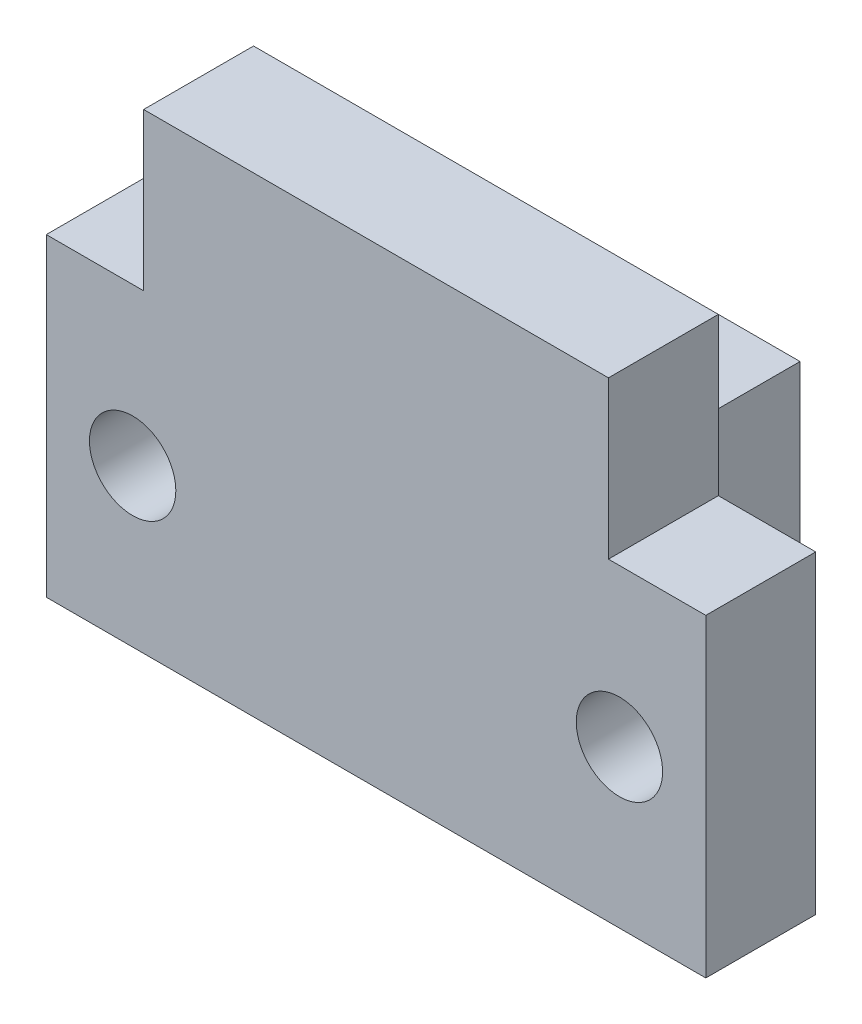
SolidWorks part; units mm, degrees
other "Encoder Spring mount spacer"
other "Encoder Spring mount"
ref_plane "Front Plane" through (0, 0, 0) normal (0, 0, 1) x (1, 0, 0)
ref_plane "Top Plane" through (0, 0, 0) normal (0, 1, 0) x (1, 0, 0)
ref_plane "Right Plane" through (0, 0, 0) normal (1, 0, 0) x (0, 0, -1)
sketch "Sketch1" plane through (0, 0, 0) normal (0, 1, 0) x (1, 0, 0)
  line L0 (10, 13.5) -> (4, 13.5)
  line L2 (21, -3.5) -> (-21, -3.5)
  line L4 (21, -3.5) -> (21, 3.5)
  line L10 (21, 3.5) -> (-21, 3.5)
  line L11 (-21, -3.5) -> (-21, 3.5)
  line L12 (0, 3.5) -> (0, -3.5) construction
  line L13 (21, 0) -> (-21, 0) construction
  line L14 (-10, 3.5) -> (-4, 3.5)
  line L15 (-10, 3.5) -> (-10, 13.5)
  line L16 (-10, 13.5) -> (-4, 13.5)
  line L17 (-4, 3.5) -> (-4, 13.5)
  line L18 (4, 3.5) -> (4, 13.5)
  line L19 (10, 3.5) -> (4, 3.5)
  line L20 (10, 3.5) -> (10, 13.5)
  point P0 (0, 0)
  dimension "D1" = 7
  dimension "D3" = 6
  dimension "D2" = 42
  dimension "D4" = 4
  dimension "D5" = 10
extrude "Boss-Extrude1" add sketch "Sketch1" along normal blind 20 contours L11 L2 L4 L10 | L10 L17 L16 L15 | L20 L0 L18 L19
sketch "Sketch6" plane through (0, 0, -3.5) normal (0, 0, -1) x (-1, 0, 0)
  line L0 (-10, 10) -> (-21, 10) construction
  line L1 (-10, 20) -> (-10, 0) construction
  line L2 (-21, 20) -> (-21, 0) construction
  line L3 (0, 0) -> (0, 20) construction
  line L4 (-4, 20) -> (4, 20) construction
  line L5 (10, 10) -> (21, 10) construction
  circle A0 centre (-15.5, 10) radius 2.75
  circle A1 centre (15.5, 10) radius 2.75
  dimension "D1" = 5.5
extrude "Cut-Extrude4" cut sketch "Sketch6" against normal through all
sketch "Sketch7" plane through (0, 0, -3.5) normal (0, 0, -1) x (-1, 0, 0)
  circle A0 centre (-15.5, 10) radius 4.5
  circle A1 centre (15.5, 10) radius 4.5
  dimension "D1" = 9
extrude "Cut-Extrude5" cut sketch "Sketch7" against normal blind 2
sketch "Sketch8" plane through (10, 0, 0) normal (1, 0, 0) x (0, 0, -1)
  line L0 (13.5, 10) -> (3.5, 10) construction
  line L1 (13.5, 20) -> (13.5, 0) construction
  line L2 (3.5, 20) -> (3.5, 0) construction
  circle A0 centre (9.5, 10) radius 1.75
  dimension "D1" = 3.5
  dimension "D2" = 4
extrude "Cut-Extrude6" cut sketch "Sketch8" against normal up to next
sketch "Sketch9" plane through (-10, 0, 0) normal (-1, 0, 0) x (0, 0, 1)
  circle A0 centre (-9.5, 10) radius 1.75
  circle A1 centre (-9.5, 10) radius 1.75 construction
extrude "Cut-Extrude7" cut sketch "Sketch9" against normal up to next
sketch "Sketch10" plane through (0, 0, 3.5) normal (0, 0, 1) x (1, 0, 0)
  line L0 (21, 20) -> (-21, 20) construction
  line L1 (-14.8, 30) -> (14.8, 30)
  line L2 (-14.8, 30) -> (-14.8, 20)
  line L3 (-14.8, 20) -> (14.8, 20)
  line L4 (14.8, 30) -> (14.8, 20)
  line L5 (0, 0) -> (0, 30) construction
  line L6 (21, 0) -> (-21, 0) construction
  dimension "D1" = 29.6
  dimension "D2" = 10
extrude "Boss-Extrude2" add sketch "Sketch10" against normal up to surface (7 mm away) up to face at (-20, 10, -3.5)
sketch "Sketch11" plane through (4, 0, 0) normal (-1, 0, 0) x (0, 0, 1)
  circle A0 centre (-9.5, 10) radius 2.5
  circle A1 centre (-9.5, 10) radius 1.75 construction
  circle A2 centre (-9.5, 10) radius 1.75
  dimension "D1" = 5
extrude "Boss-Extrude3" add sketch "Sketch11" along normal offset from surface (7.6 mm away) 0.4 separate body up to face at (-4, 10, -7.75)
other "Save Bodies1"
